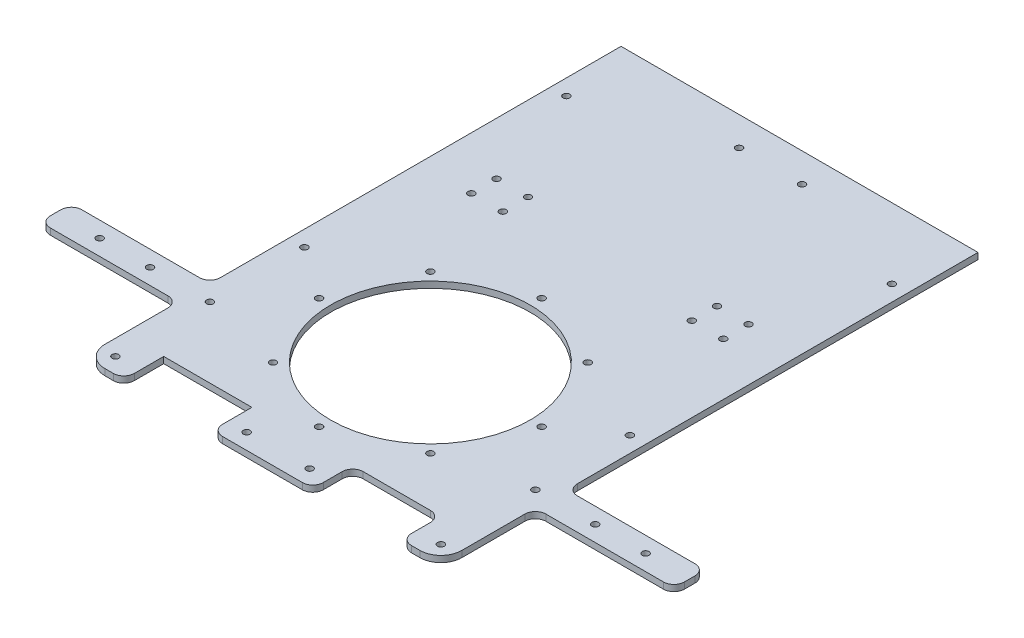
SolidWorks part; units mm, degrees
ref_plane "Front Plane" through (0, 0, 0) normal (0, 0, 1) x (1, 0, 0)
ref_plane "Top Plane" through (0, 0, 0) normal (0, 1, 0) x (1, 0, 0)
ref_plane "Right Plane" through (0, 0, 0) normal (1, 0, 0) x (0, 0, -1)
sketch "Sketch1" plane through (0, 0, 0) normal (0, 1, 0) x (1, 0, 0)
  line L4 (0, 0) -> (170, 0)
  line L5 (0, 0) -> (0, 330) construction
  line L6 (0, 330) -> (170, 330) construction
  line L7 (170, 0) -> (170, 330) construction
  line L8 (85, 330) -> (225, 367.5129)
  line L9 (-55, 367.5129) -> (85, 330)
  line L10 (-55, 367.5129) -> (-55, 300)
  line L11 (-55, 300) -> (0, 300)
  line L12 (225, 300) -> (225, 367.5129)
  line L13 (225, 300) -> (170, 300)
  line L14 (0, 300) -> (0, 0)
  line L15 (170, 300) -> (170, 0)
  dimension "D1" = 30
  dimension "D2" = 330
  dimension "D3" = 15
  dimension "D4" = 15
  dimension "D5" = 55
  dimension "D6" = 170
extrude "Boss-Extrude1" add sketch "Sketch1" along normal blind 3
fillet "Fillet1" radius 200 1 edges at (85, 1.5, -330)
fillet "Fillet2" radius 10 8 edges at (0, 1.5, 0) (170, 1.5, 0) (170, 1.5, -300) (0, 1.5, -300) (-55, 1.5, -300) (225, 1.5, -300) (225, 1.5, -367.5129) (-55, 1.5, -367.5129)
sketch "Sketch2" plane through (0, 3, 0) normal (0, 1, 0) x (1, 0, 0)
  line L0 (85, 337.0552) -> (85, 0)
  line L1 (10, 0) -> (160, 0) construction
  line L2 (0, 32.5) -> (170, 32.5) construction
  line L3 (0, 290) -> (0, 10) construction
  line L4 (170, 10) -> (170, 290) construction
  circle A0 centre (85, 80) radius 47.5
  arc A1 (33.2362, 343.8701) -> (136.7638, 343.8701) centre (85, 537.0552) ccw construction
  dimension "D1" = 95
  dimension "D2" = 32.5
extrude "Cut-Extrude2" cut sketch "Sketch2" against normal through all contours L0 A0 | L0 A0
sketch "Sketch3" plane through (0, 3, 0) normal (0, 1, 0) x (1, 0, 0)
  line L1 (19, 278.8) -> (61, 278.8)
  line L2 (19, 278.8) -> (19, 255.8)
  line L3 (19, 255.8) -> (61, 255.8)
  line L4 (61, 278.8) -> (61, 255.8)
  line L5 (109, 278.8) -> (151, 278.8)
  line L6 (109, 278.8) -> (109, 255.8)
  line L7 (109, 255.8) -> (151, 255.8)
  line L8 (151, 278.8) -> (151, 255.8)
  line L9 (19, 19) -> (61, 19)
  line L10 (19, 19) -> (19, 0)
  line L11 (19, 0) -> (61, 0)
  line L12 (61, 19) -> (61, 0)
  line L13 (109, 19) -> (151, 19)
  line L14 (109, 19) -> (109, 0)
  line L15 (109, 0) -> (151, 0)
  line L16 (151, 19) -> (151, 0)
  line L17 (-45, 300) -> (-10, 300) construction
  line L18 (0, 290) -> (0, 10) construction
  line L19 (170, 10) -> (170, 290) construction
  line L20 (280, 0) -> (-110, 0) construction
  dimension "D1" = 21.2
  dimension "D2" = 23
  dimension "D3" = 19
  dimension "D4" = 42
  dimension "D5" = 19
  dimension "D6" = 19
extrude "Cut-Extrude3" cut sketch "Sketch3" against normal through all
sketch "Sketch4" plane through (0, 3, 0) normal (0, 1, 0) x (1, 0, 0)
  circle A0 centre (85, 80) radius 58 construction
  circle A1 centre (85, 80) radius 53 construction
  circle A2 centre (85, 133) radius 1.6
  circle A3 centre (122.4767, 117.4767) radius 1.6
  circle A4 centre (138, 80) radius 1.6
  circle A5 centre (122.4767, 42.5233) radius 1.6
  circle A6 centre (85, 27) radius 1.6
  circle A7 centre (47.5233, 42.5233) radius 1.6
  circle A8 centre (32, 80) radius 1.6
  circle A9 centre (47.5233, 117.4767) radius 1.6
  point P22 (85, 80)
  dimension "D1" = 116
  dimension "D2" = 5
  dimension "D3" = 3.2
  dimension "D4" = 8
extrude "Cut-Extrude5" cut sketch "Sketch4" against normal through all
sketch "Sketch5" plane through (0, 3, 0) normal (0, 1, 0) x (1, 0, 0)
  circle A0 centre (7.5, 312) radius 1.6
  circle A1 centre (7.5, 267.3) radius 1.6
  circle A2 centre (7.5, 222.3) radius 1.6
  circle A3 centre (7.5, 97.5) radius 1.6
  circle A4 centre (7.5, 7.5) radius 1.6
  circle A5 centre (7.5, 52.5) radius 1.6
  circle A6 centre (70, 7.5) radius 1.6
  circle A7 centre (100, 7.5) radius 1.6
  circle A8 centre (162.5, 7.5) radius 1.6
  circle A9 centre (162.5, 52.5) radius 1.6
  circle A10 centre (162.5, 97.5) radius 1.6
  circle A11 centre (162.5, 222.3) radius 1.6
  circle A12 centre (162.5, 267.3) radius 1.6
  circle A13 centre (162.5, 312) radius 1.6
  circle A14 centre (162.5, 342.755) radius 1.6
  circle A15 centre (109.3378, 328.5102) radius 1.6
  circle A16 centre (60.6622, 328.5102) radius 1.6
  circle A17 centre (7.5, 342.755) radius 1.6
  circle A18 centre (70, 267.5) radius 1.6
  circle A19 centre (100, 267.5) radius 1.6
  dimension "D1" = 3.2
extrude "Cut-Extrude6" cut sketch "Sketch5" against normal through all
sketch "Sketch6" plane through (0, 0, 0) normal (0, -1, 0) x (1, 0, 0)
  line L6 (0, -290) -> (0, -10) construction
  line L7 (0, -45) -> (-66, -45)
  line L8 (0, -45) -> (0, -60)
  line L9 (0, -60) -> (-66, -60)
  line L10 (-66, -45) -> (-66, -60)
  line L11 (0, -45) -> (-66, -45) construction
  line L12 (170, -10) -> (170, -290) construction
  line L13 (170, -60) -> (236, -60)
  line L14 (170, -60) -> (170, -45)
  line L15 (170, -45) -> (236, -45)
  line L16 (236, -60) -> (236, -45)
  line L17 (170, -60) -> (236, -60) construction
  circle A0 centre (191, -52.5) radius 1.6
  circle A1 centre (215, -52.5) radius 1.6
  circle A2 centre (-45, -52.5) radius 1.6
  circle A3 centre (-21, -52.5) radius 1.6
  dimension "D3" = 66
  dimension "D5" = 3.2
  dimension "D1" = 66
  dimension "D2" = 15
  dimension "D4" = 15
extrude "Boss-Extrude2" add sketch "Sketch6" against normal blind 3
fillet "Fillet3" radius 5 14 edges at (236, 1.5, -60) (236, 1.5, -45) (-66, 1.5, -45) (-66, 1.5, -60) (0, 1.5, -60) (0, 1.5, -45) (151, 1.5, 0) (151, 1.5, -19) (109, 1.5, -19) (109, 1.5, 0) (61, 1.5, 0) (19, 1.5, 0) (170, 1.5, -60) (170, 1.5, -45)
sketch "Sketch7" plane through (0, 3, 0) normal (0, 1, 0) x (1, 0, 0)
  circle A0 centre (130, 171.5) radius 1.6
  circle A1 centre (145, 171.5) radius 1.6
  circle A2 centre (145, 159.5) radius 1.6
  circle A3 centre (130, 159.5) radius 1.6
  circle A4 centre (25, 171.5) radius 1.6
  circle A5 centre (40, 171.5) radius 1.6
  circle A6 centre (40, 159.5) radius 1.6
  circle A7 centre (25, 159.5) radius 1.6
  circle A8 centre (70, 242) radius 1.6
  circle A9 centre (100, 242) radius 1.6
  dimension "D1" = 3.2
extrude "Cut-Extrude7" cut sketch "Sketch7" against normal through all
sketch "Sketch8" plane through (0, 3, 0) normal (0, 1, 0) x (1, 0, 0)
  line L0 (-45, 364.4806) -> (215, 364.4806)
  line L1 (215, 364.4806) -> (136.7638, 343.8701)
  line L2 (136.7638, 343.8701) -> (33.2362, 343.8701) construction
  line L3 (33.2362, 343.8701) -> (-45, 364.4806)
  arc A0 (-42.4118, 364.1399) -> (-55, 354.4806) centre (-45, 354.4806) ccw construction
  arc A1 (225, 354.4806) -> (212.4118, 364.1399) centre (215, 354.4806) ccw construction
  arc A2 (33.2362, 343.8701) -> (136.7638, 343.8701) centre (85, 537.0552) ccw
  arc A3 (33.2362, 343.8701) -> (136.7638, 343.8701) centre (85, 537.0552) ccw construction
extrude "Boss-Extrude4" [suppressed] add sketch "Sketch8" against normal blind 3
sketch "Sketch9" plane through (0, 3, 0) normal (0, 1, 0) x (1, 0, 0)
  line L0 (-55, 354.4806) -> (-55, 310) construction
  line L1 (-45, 300) -> (-10, 300) construction
  line L2 (-55, 335) -> (-5, 335) construction
  line L3 (-5, 335) -> (-5, 300) construction
  line L4 (-45, 307.5) -> (-45, 327.5) construction
  line L5 (-45, 327.5) -> (-15, 327.5) construction
  line L6 (-15, 327.5) -> (-15, 307.5) construction
  line L7 (-15, 307.5) -> (-45, 307.5) construction
  line L8 (85, 337.0552) -> (85, 300) construction
  circle A0 centre (-45, 307.5) radius 1.6
  circle A1 centre (-15, 307.5) radius 1.6
  circle A2 centre (-45, 327.5) radius 1.6
  circle A3 centre (-15, 327.5) radius 1.6
  arc A4 (33.2362, 343.8701) -> (136.7638, 343.8701) centre (85, 537.0552) ccw construction
  circle A5 centre (185, 307.5) radius 1.6
  circle A6 centre (185, 327.5) radius 1.6
  circle A7 centre (215, 307.5) radius 1.6
  circle A8 centre (215, 327.5) radius 1.6
  dimension "D1" = 10
  dimension "D2" = 7.5
  dimension "D7" = 3.2
  dimension "D3" = 35
  dimension "D4" = 50
  dimension "D5" = 7.5
  dimension "D6" = 10
extrude "Cut-Extrude8" cut sketch "Sketch9" against normal through all
sketch "Sketch10" plane through (0, 3, 0) normal (0, 1, 0) x (1, 0, 0)
  line L0 (19, 255.8) -> (61, 255.8) construction
  line L1 (-55, 255.8) -> (225, 255.8)
  line L2 (-55, 255.8) -> (-55, 364.4806)
  line L3 (-55, 364.4806) -> (225, 364.4806)
  line L4 (225, 255.8) -> (225, 364.4806)
  line L5 (-55, 354.4806) -> (-55, 310) construction
  line L6 (225, 310) -> (225, 354.4806) construction
  arc A0 (-42.4118, 364.1399) -> (-55, 354.4806) centre (-45, 354.4806) ccw construction
extrude "Cut-Extrude9" cut sketch "Sketch10" against normal blind 10
